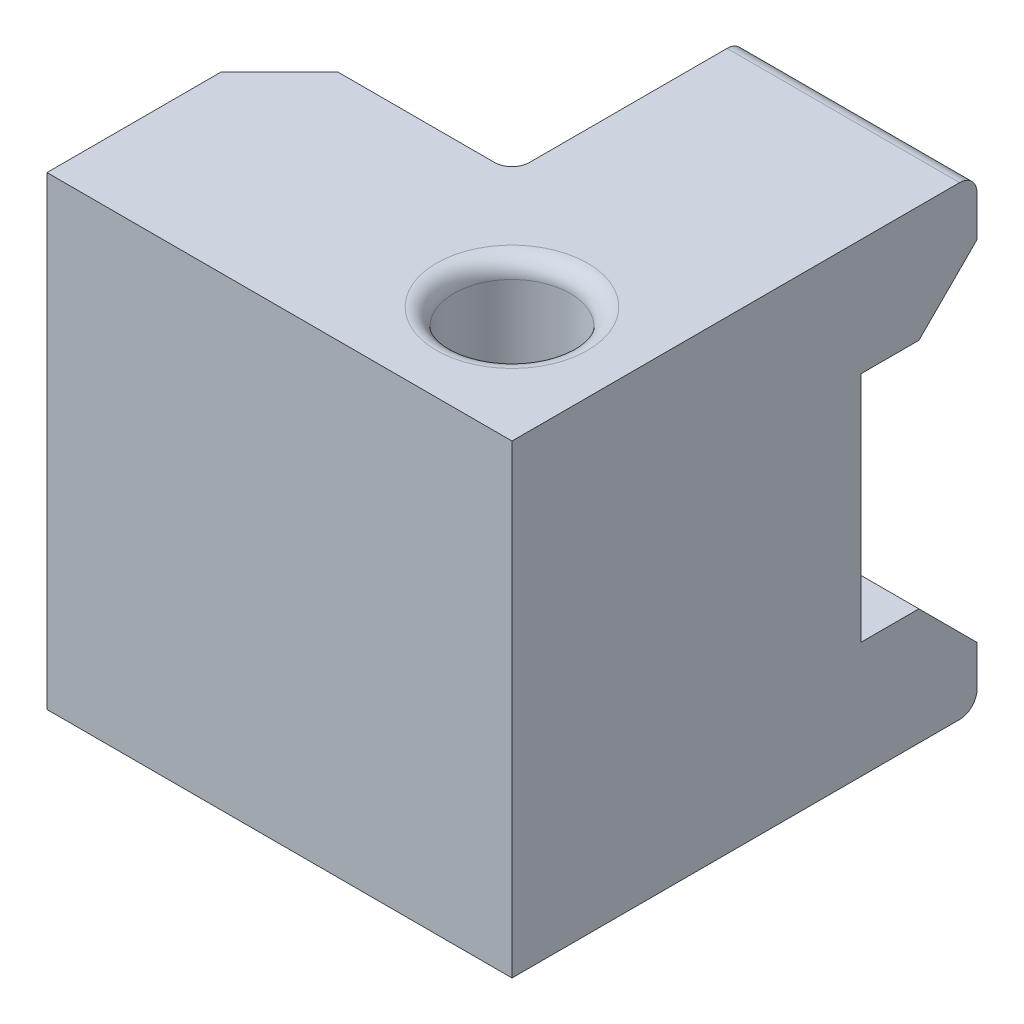
SolidWorks part; units mm, degrees
ref_plane "Front Plane" through (0, 0, 0) normal (0, 0, 1) x (1, 0, 0)
ref_plane "Top Plane" through (0, 0, 0) normal (0, 1, 0) x (1, 0, 0)
ref_plane "Right Plane" through (0, 0, 0) normal (1, 0, 0) x (0, 0, -1)
sketch "Sketch2" plane through (0, 0, 0) normal (0, 1, 0) x (1, 0, 0)
  line L0 (0, 0) -> (-80, 0)
  line L1 (-80, 0) -> (-80, 40)
  line L2 (-80, 40) -> (-40, 40)
  line L3 (-40, 40) -> (-40, 80)
  line L4 (-40, 80) -> (0, 80)
  line L5 (0, 80) -> (0, 0)
  circle A0 centre (-20, 20) radius 10
  dimension "D5" = 20
  dimension "D1" = 80
  dimension "D2" = 40
  dimension "D3" = 80
  dimension "D4" = 40
  dimension "D6" = 20
  dimension "D7" = 20
extrude "Boss-Extrude1" add sketch "Sketch2" along normal blind 80
sketch "Sketch4" plane through (0, 0, 0) normal (1, 0, 0) x (0, 0, -1)
  line L0 (80, 60) -> (60, 60)
  line L1 (80, 80) -> (80, 0) construction
  line L2 (60, 60) -> (60, 20)
  line L3 (60, 20) -> (80, 20)
  line L4 (80, 20) -> (80, 60)
  line L5 (0, 80) -> (80, 80) construction
  line L6 (0, 0) -> (80, 0) construction
  dimension "D1" = 20
  dimension "D2" = 20
  dimension "D3" = 20
extrude "Cut-Extrude1" cut sketch "Sketch4" against normal through all
fillet "Fillet1" radius 3 1 edges at (-20, 0, -80)
fillet "Fillet2" radius 3 1 edges at (-20, 80, -80)
chamfer "Chamfer1" distance 10 angle 45 1 edges at (-20, 60, -80)
chamfer "Chamfer2" distance 10 angle 45 1 edges at (-20, 20, -80)
chamfer "Chamfer3" distance 10 angle 45 1 edges at (-80, 40, -40)
fillet "Fillet4" radius 3 1 edges at (-40, 40, -40)
fillet "Fillet5" radius 3 1 edges at (-20, 0, -10)
fillet "Fillet6" radius 3 1 edges at (-20, 80, -10)
